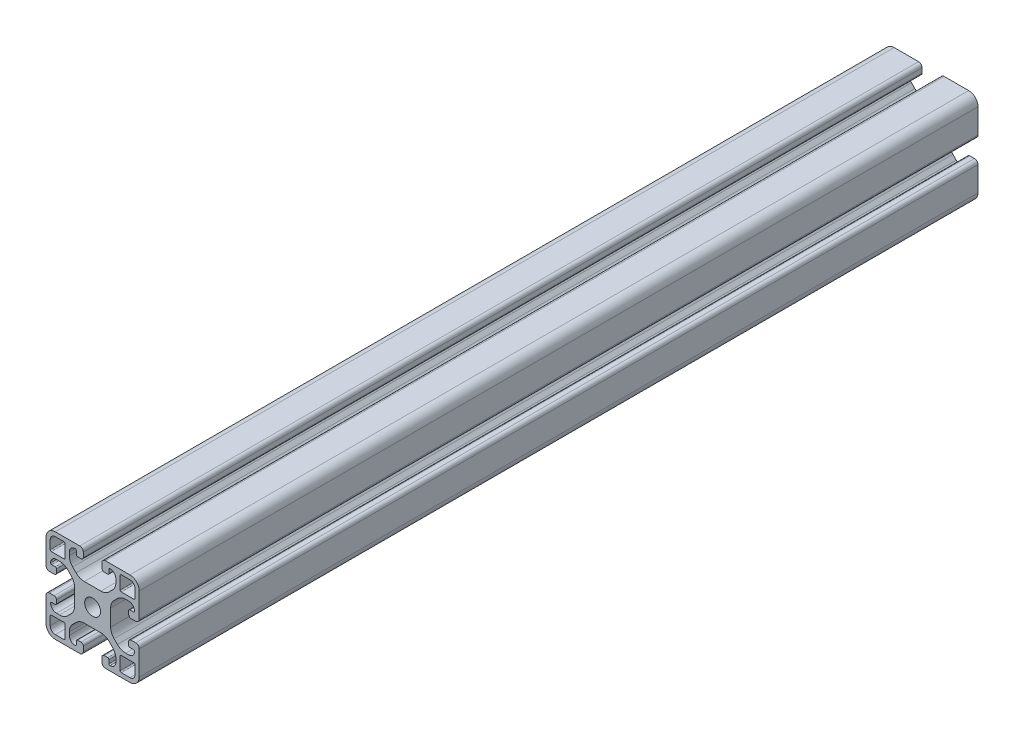
SolidWorks part; units mm, degrees
ref_plane "Front" through (0, 0, 0) normal (0, 0, 1) x (1, 0, 0)
ref_plane "Top" through (0, 0, 0) normal (0, 1, 0) x (1, 0, 0)
ref_plane "Right" through (0, 0, 0) normal (1, 0, 0) x (0, 0, -1)
sketch "Sketch1" plane through (0, 0, 0) normal (0, 0, 1) x (1, 0, 0)
  line L0 (226.845, 367.6546) -> (226.845, 357.1546)
  line L1 (228.345, 355.6546) -> (230.345, 355.6546)
  line L2 (231.345, 356.6546) -> (231.345, 358.1546)
  line L3 (230.845, 358.6546) -> (229.345, 358.6546)
  line L4 (231.345, 361.6546) -> (232.6526, 361.6546)
  line L5 (236.1881, 360.1902) -> (237.6305, 358.7478)
  line L6 (239.095, 355.2122) -> (239.095, 351.6546)
  line L7 (239.095, 351.6546) -> (239.095, 348.097)
  line L8 (237.6305, 344.5615) -> (236.1881, 343.1191)
  line L9 (232.6526, 341.6546) -> (231.345, 341.6546)
  line L10 (229.345, 344.6546) -> (230.845, 344.6546)
  line L11 (231.345, 345.1546) -> (231.345, 346.6546)
  line L12 (230.345, 347.6546) -> (228.345, 347.6546)
  line L13 (226.845, 346.1546) -> (226.845, 335.6546)
  line L14 (230.845, 331.6546) -> (241.345, 331.6546)
  line L15 (242.845, 333.1546) -> (242.845, 335.1546)
  line L16 (241.845, 336.1546) -> (240.345, 336.1546)
  line L17 (239.845, 335.6546) -> (239.845, 334.1546)
  line L18 (236.845, 336.1546) -> (236.845, 337.4622)
  line L19 (238.3095, 340.9978) -> (239.7518, 342.4402)
  line L20 (243.2874, 343.9046) -> (246.845, 343.9046)
  line L21 (246.845, 343.9046) -> (250.4026, 343.9046)
  line L22 (253.9381, 342.4402) -> (255.3805, 340.9978)
  line L23 (256.845, 337.4622) -> (256.845, 336.1546)
  line L24 (253.845, 334.1546) -> (253.845, 335.6546)
  line L25 (253.345, 336.1546) -> (251.845, 336.1546)
  line L26 (250.845, 335.1546) -> (250.845, 333.1546)
  line L27 (252.345, 331.6546) -> (262.845, 331.6546)
  line L28 (266.845, 335.6546) -> (266.845, 346.1546)
  line L29 (265.345, 347.6546) -> (263.345, 347.6546)
  line L30 (262.345, 346.6546) -> (262.345, 345.1546)
  line L31 (262.845, 344.6546) -> (264.345, 344.6546)
  line L32 (262.345, 341.6546) -> (261.0374, 341.6546)
  line L33 (257.5018, 343.1191) -> (256.0595, 344.5615)
  line L34 (254.595, 348.097) -> (254.595, 351.6546)
  line L35 (254.595, 351.6546) -> (254.595, 355.2122)
  line L36 (256.0595, 358.7478) -> (257.5018, 360.1902)
  line L37 (261.0374, 361.6546) -> (262.345, 361.6546)
  line L38 (264.345, 358.6546) -> (262.845, 358.6546)
  line L39 (262.345, 358.1546) -> (262.345, 356.6546)
  line L40 (263.345, 355.6546) -> (265.345, 355.6546)
  line L41 (266.845, 357.1546) -> (266.845, 367.6546)
  line L42 (262.845, 371.6546) -> (252.345, 371.6546)
  line L43 (250.845, 370.1546) -> (250.845, 368.1546)
  line L44 (251.845, 367.1546) -> (253.345, 367.1546)
  line L45 (253.845, 367.6546) -> (253.845, 369.1546)
  line L46 (256.845, 367.1546) -> (256.845, 365.847)
  line L47 (255.3805, 362.3115) -> (253.9381, 360.8691)
  line L48 (250.4026, 359.4046) -> (246.845, 359.4046)
  line L49 (246.845, 359.4046) -> (243.2874, 359.4046)
  line L50 (239.7518, 360.8691) -> (238.3095, 362.3115)
  line L51 (236.845, 365.847) -> (236.845, 367.1546)
  line L52 (239.845, 369.1546) -> (239.845, 367.6546)
  line L53 (240.345, 367.1546) -> (241.845, 367.1546)
  line L54 (242.845, 368.1546) -> (242.845, 370.1546)
  line L55 (241.345, 371.6546) -> (230.845, 371.6546)
  line L56 (235.045, 333.9546) -> (235.045, 339.3546)
  line L57 (234.545, 339.8546) -> (229.145, 339.8546)
  line L58 (228.645, 339.3546) -> (228.645, 335.6546)
  line L59 (230.845, 333.4546) -> (234.545, 333.4546)
  line L60 (229.145, 363.4546) -> (234.545, 363.4546)
  line L61 (235.045, 363.9546) -> (235.045, 369.3546)
  line L62 (234.545, 369.8546) -> (230.845, 369.8546)
  line L63 (228.645, 367.6546) -> (228.645, 363.9546)
  line L64 (264.545, 339.8546) -> (259.145, 339.8546)
  line L65 (258.645, 339.3546) -> (258.645, 333.9546)
  line L66 (259.145, 333.4546) -> (262.845, 333.4546)
  line L67 (265.045, 335.6546) -> (265.045, 339.3546)
  line L68 (258.645, 369.3546) -> (258.645, 363.9546)
  line L69 (259.145, 363.4546) -> (264.545, 363.4546)
  line L70 (265.045, 363.9546) -> (265.045, 367.6546)
  line L71 (262.845, 369.8546) -> (259.145, 369.8546)
  circle A0 centre (246.845, 351.6546) radius 3.4
  arc A1 (226.845, 357.1546) -> (228.345, 355.6546) centre (228.345, 357.1546) ccw
  arc A2 (230.345, 355.6546) -> (231.345, 356.6546) centre (230.345, 356.6546) ccw
  arc A3 (231.345, 358.1546) -> (230.845, 358.6546) centre (230.845, 358.1546) ccw
  arc A4 (229.345, 358.6546) -> (228.845, 359.1546) centre (229.345, 359.1546) cw
  arc A5 (228.845, 359.1546) -> (231.345, 361.6546) centre (231.345, 359.1546) cw
  arc A6 (232.6526, 361.6546) -> (236.1881, 360.1902) centre (232.6526, 356.6546) cw
  arc A7 (237.6305, 358.7478) -> (239.095, 355.2122) centre (234.095, 355.2122) cw
  arc A8 (239.095, 348.097) -> (237.6305, 344.5615) centre (234.095, 348.097) cw
  arc A9 (236.1881, 343.1191) -> (232.6526, 341.6546) centre (232.6526, 346.6546) cw
  arc A10 (231.345, 341.6546) -> (228.845, 344.1546) centre (231.345, 344.1546) cw
  arc A11 (228.845, 344.1546) -> (229.345, 344.6546) centre (229.345, 344.1546) cw
  arc A12 (230.845, 344.6546) -> (231.345, 345.1546) centre (230.845, 345.1546) ccw
  arc A13 (231.345, 346.6546) -> (230.345, 347.6546) centre (230.345, 346.6546) ccw
  arc A14 (228.345, 347.6546) -> (226.845, 346.1546) centre (228.345, 346.1546) ccw
  arc A15 (226.845, 335.6546) -> (230.845, 331.6546) centre (230.845, 335.6546) ccw
  arc A16 (241.345, 331.6546) -> (242.845, 333.1546) centre (241.345, 333.1546) ccw
  arc A17 (242.845, 335.1546) -> (241.845, 336.1546) centre (241.845, 335.1546) ccw
  arc A18 (240.345, 336.1546) -> (239.845, 335.6546) centre (240.345, 335.6546) ccw
  arc A19 (239.845, 334.1546) -> (239.345, 333.6546) centre (239.345, 334.1546) cw
  arc A20 (239.345, 333.6546) -> (236.845, 336.1546) centre (239.345, 336.1546) cw
  arc A21 (236.845, 337.4622) -> (238.3095, 340.9978) centre (241.845, 337.4622) cw
  arc A22 (239.7518, 342.4402) -> (243.2874, 343.9046) centre (243.2874, 338.9046) cw
  arc A23 (250.4026, 343.9046) -> (253.9381, 342.4402) centre (250.4026, 338.9046) cw
  arc A24 (255.3805, 340.9978) -> (256.845, 337.4622) centre (251.845, 337.4622) cw
  arc A25 (256.845, 336.1546) -> (254.345, 333.6546) centre (254.345, 336.1546) cw
  arc A26 (254.345, 333.6546) -> (253.845, 334.1546) centre (254.345, 334.1546) cw
  arc A27 (253.845, 335.6546) -> (253.345, 336.1546) centre (253.345, 335.6546) ccw
  arc A28 (251.845, 336.1546) -> (250.845, 335.1546) centre (251.845, 335.1546) ccw
  arc A29 (250.845, 333.1546) -> (252.345, 331.6546) centre (252.345, 333.1546) ccw
  arc A30 (262.845, 331.6546) -> (266.845, 335.6546) centre (262.845, 335.6546) ccw
  arc A31 (266.845, 346.1546) -> (265.345, 347.6546) centre (265.345, 346.1546) ccw
  arc A32 (263.345, 347.6546) -> (262.345, 346.6546) centre (263.345, 346.6546) ccw
  arc A33 (262.345, 345.1546) -> (262.845, 344.6546) centre (262.845, 345.1546) ccw
  arc A34 (264.345, 344.6546) -> (264.845, 344.1546) centre (264.345, 344.1546) cw
  arc A35 (264.845, 344.1546) -> (262.345, 341.6546) centre (262.345, 344.1546) cw
  arc A36 (261.0374, 341.6546) -> (257.5018, 343.1191) centre (261.0374, 346.6546) cw
  arc A37 (256.0595, 344.5615) -> (254.595, 348.097) centre (259.595, 348.097) cw
  arc A38 (254.595, 355.2122) -> (256.0595, 358.7478) centre (259.595, 355.2122) cw
  arc A39 (257.5018, 360.1902) -> (261.0374, 361.6546) centre (261.0374, 356.6546) cw
  arc A40 (262.345, 361.6546) -> (264.845, 359.1546) centre (262.345, 359.1546) cw
  arc A41 (264.845, 359.1546) -> (264.345, 358.6546) centre (264.345, 359.1546) cw
  arc A42 (262.845, 358.6546) -> (262.345, 358.1546) centre (262.845, 358.1546) ccw
  arc A43 (262.345, 356.6546) -> (263.345, 355.6546) centre (263.345, 356.6546) ccw
  arc A44 (265.345, 355.6546) -> (266.845, 357.1546) centre (265.345, 357.1546) ccw
  arc A45 (266.845, 367.6546) -> (262.845, 371.6546) centre (262.845, 367.6546) ccw
  arc A46 (252.345, 371.6546) -> (250.845, 370.1546) centre (252.345, 370.1546) ccw
  arc A47 (250.845, 368.1546) -> (251.845, 367.1546) centre (251.845, 368.1546) ccw
  arc A48 (253.345, 367.1546) -> (253.845, 367.6546) centre (253.345, 367.6546) ccw
  arc A49 (253.845, 369.1546) -> (254.345, 369.6546) centre (254.345, 369.1546) cw
  arc A50 (254.345, 369.6546) -> (256.845, 367.1546) centre (254.345, 367.1546) cw
  arc A51 (256.845, 365.847) -> (255.3805, 362.3115) centre (251.845, 365.847) cw
  arc A52 (253.9381, 360.8691) -> (250.4026, 359.4046) centre (250.4026, 364.4046) cw
  arc A53 (243.2874, 359.4046) -> (239.7518, 360.8691) centre (243.2874, 364.4046) cw
  arc A54 (238.3095, 362.3115) -> (236.845, 365.847) centre (241.845, 365.847) cw
  arc A55 (236.845, 367.1546) -> (239.345, 369.6546) centre (239.345, 367.1546) cw
  arc A56 (239.345, 369.6546) -> (239.845, 369.1546) centre (239.345, 369.1546) cw
  arc A57 (239.845, 367.6546) -> (240.345, 367.1546) centre (240.345, 367.6546) ccw
  arc A58 (241.845, 367.1546) -> (242.845, 368.1546) centre (241.845, 368.1546) ccw
  arc A59 (242.845, 370.1546) -> (241.345, 371.6546) centre (241.345, 370.1546) ccw
  arc A60 (230.845, 371.6546) -> (226.845, 367.6546) centre (230.845, 367.6546) ccw
  arc A61 (235.045, 339.3546) -> (234.545, 339.8546) centre (234.545, 339.3546) ccw
  arc A62 (229.145, 339.8546) -> (228.645, 339.3546) centre (229.145, 339.3546) ccw
  arc A63 (228.645, 335.6546) -> (230.845, 333.4546) centre (230.845, 335.6546) ccw
  arc A64 (234.545, 333.4546) -> (235.045, 333.9546) centre (234.545, 333.9546) ccw
  arc A65 (228.645, 363.9546) -> (229.145, 363.4546) centre (229.145, 363.9546) ccw
  arc A66 (234.545, 363.4546) -> (235.045, 363.9546) centre (234.545, 363.9546) ccw
  arc A67 (235.045, 369.3546) -> (234.545, 369.8546) centre (234.545, 369.3546) ccw
  arc A68 (230.845, 369.8546) -> (228.645, 367.6546) centre (230.845, 367.6546) ccw
  arc A69 (265.045, 339.3546) -> (264.545, 339.8546) centre (264.545, 339.3546) ccw
  arc A70 (259.145, 339.8546) -> (258.645, 339.3546) centre (259.145, 339.3546) ccw
  arc A71 (258.645, 333.9546) -> (259.145, 333.4546) centre (259.145, 333.9546) ccw
  arc A72 (262.845, 333.4546) -> (265.045, 335.6546) centre (262.845, 335.6546) ccw
  arc A73 (258.645, 363.9546) -> (259.145, 363.4546) centre (259.145, 363.9546) ccw
  arc A74 (264.545, 363.4546) -> (265.045, 363.9546) centre (264.545, 363.9546) ccw
  arc A75 (265.045, 367.6546) -> (262.845, 369.8546) centre (262.845, 367.6546) ccw
  arc A76 (259.145, 369.8546) -> (258.645, 369.3546) centre (259.145, 369.3546) ccw
  point P189 (226.845, 331.6546)
  point P190 (226.845, 351.6546)
  point P191 (231.345, 351.6546)
  point P192 (246.845, 331.6546)
  point P193 (246.845, 336.1546)
  point P205 (231.302, 356.3646)
  point P206 (231.302, 356.3646)
  point P207 (226.845, 371.6546)
  point P208 (246.845, 367.1546)
  point P209 (246.845, 371.6546)
  point P221 (266.845, 331.6546)
  point P222 (262.345, 351.6546)
  point P223 (266.845, 351.6546)
  point P235 (266.845, 371.6546)
extrude "Base-Extrude" add sketch "Sketch1" along normal blind 360
ref_plane "Plane1" through (0, 0, 180) normal (0, 0, 1) x (1, 0, 0)
